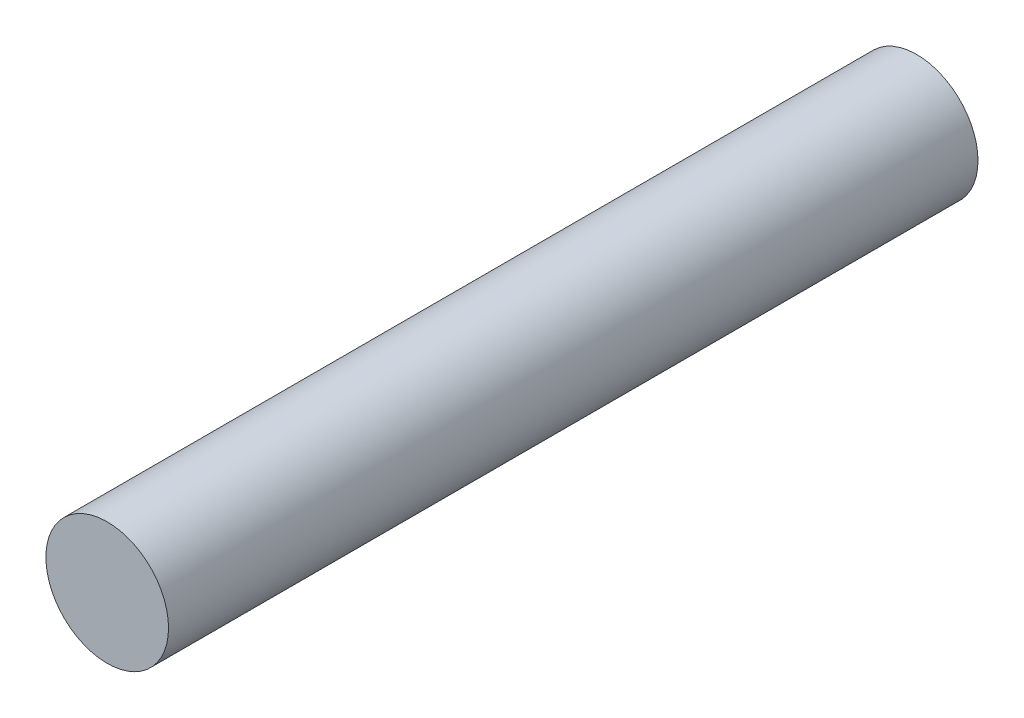
SolidWorks part; units mm, degrees
ref_plane "Front Plane" through (0, 0, 0) normal (0, 0, 1) x (1, 0, 0)
ref_plane "Top Plane" through (0, 0, 0) normal (0, 1, 0) x (1, 0, 0)
ref_plane "Right Plane" through (0, 0, 0) normal (1, 0, 0) x (0, 0, -1)
sketch "Sketch1" plane through (0, 0, 0) normal (0, 0, 1) x (1, 0, 0)
  circle A0 centre (0, 0) radius 2.5
  dimension "D1" = 5
extrude "Boss-Extrude1" add sketch "Sketch1" along normal blind 33
